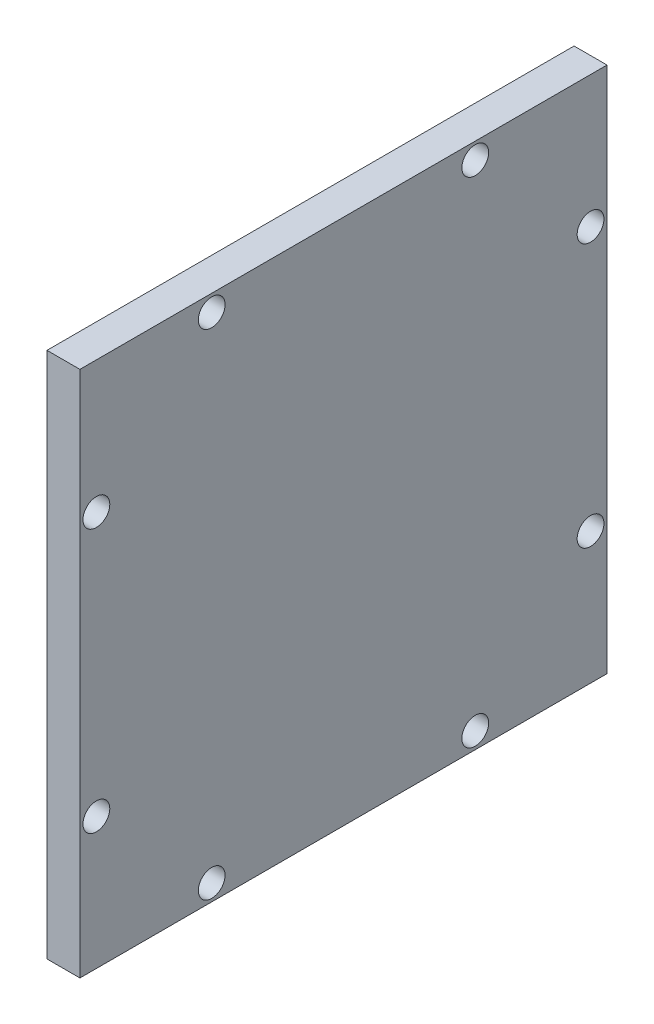
SolidWorks part; units mm, degrees
ref_plane "Front Plane" through (0, 0, 0) normal (0, 0, 1) x (1, 0, 0)
ref_plane "Top Plane" through (0, 0, 0) normal (0, 1, 0) x (1, 0, 0)
ref_plane "Right Plane" through (0, 0, 0) normal (1, 0, 0) x (0, 0, -1)
sketch "Sketch1" plane through (0, 0, 0) normal (1, 0, 0) x (0, 0, -1)
  line L1 (0, 0) -> (48, 0)
  line L2 (0, 0) -> (0, 48)
  line L3 (0, 48) -> (48, 48)
  line L4 (48, 0) -> (48, 48)
extrude "Boss-Extrude1" add sketch "Sketch1" along normal blind 3
sketch "Sketch4" plane through (3, 0, 0) normal (1, 0, 0) x (0, 0, -1)
  line L0 (0, 48) -> (3, 48)
  line L1 (48, 48) -> (0, 48) construction
  line L2 (3, 48) -> (3, 0)
  line L3 (0, 0) -> (48, 0) construction
  line L4 (48, 48) -> (45, 48)
  line L5 (45, 48) -> (45, 0)
  line L6 (1.5, 48) -> (1.5, 0)
  line L7 (46.5, 48) -> (46.5, 0)
  line L8 (0, 24) -> (48, 24)
  line L9 (0, 48) -> (0, 0) construction
  line L10 (48, 0) -> (48, 48) construction
  line L11 (0, 48) -> (0, 45)
  line L12 (0, 45) -> (48, 45)
  line L13 (0, 0) -> (0, 3)
  line L14 (0, 3) -> (48, 3)
  line L15 (0, 1.5) -> (48, 1.5)
  line L16 (0, 46.5) -> (48, 46.5)
  line L17 (24, 48) -> (24, 0)
  line L18 (0, 3) -> (24, 0)
  line L19 (24, 0) -> (48, 3)
  line L20 (24, 45) -> (0, 48)
  line L21 (24, 45) -> (48, 48)
  line L22 (0, 48) -> (3, 24)
  line L23 (3, 24) -> (0, 0)
  line L24 (48, 48) -> (45, 24)
  line L25 (45, 24) -> (48, 0)
sketch "Sketch11" plane through (3, 0, 0) normal (1, 0, 0) x (0, 0, -1)
  line L0 (24, 45) -> (0, 48) construction
  line L1 (24, 45) -> (48, 48) construction
  line L2 (0, 3) -> (24, 0) construction
  line L3 (24, 0) -> (48, 3) construction
  line L4 (0, 48) -> (3, 24) construction
  line L5 (3, 24) -> (0, 0) construction
  line L6 (48, 48) -> (45, 24) construction
  line L7 (45, 24) -> (48, 0) construction
  circle A0 centre (12, 46.5) radius 1.22
  circle A1 centre (36, 46.5) radius 1.22
  circle A2 centre (12, 1.5) radius 1.22
  circle A3 centre (36, 1.5) radius 1.22
  circle A4 centre (1.5, 36) radius 1.22
  circle A5 centre (1.5, 12) radius 1.22
  circle A6 centre (46.5, 36) radius 1.22
  circle A7 centre (46.5, 12) radius 1.22
extrude "Cut-Extrude1" cut sketch "Sketch11" against normal blind 3
